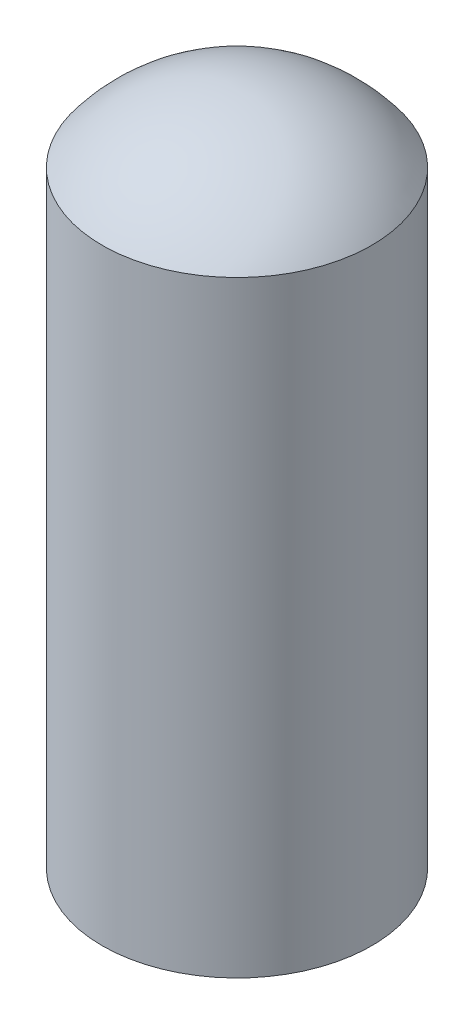
SolidWorks part; units mm, degrees
ref_plane "Front Plane" through (0, 0, 0) normal (0, 0, 1) x (1, 0, 0)
ref_plane "Top Plane" through (0, 0, 0) normal (0, 1, 0) x (1, 0, 0)
ref_plane "Right Plane" through (0, 0, 0) normal (1, 0, 0) x (0, 0, -1)
sketch "Sketch1" plane through (0, 0, 0) normal (0, 0, 1) x (1, 0, 0)
  line L0 (0, 0) -> (-4, 0)
  line L1 (-4, 0) -> (-4, 18)
  line L2 (0, 0) -> (0, 20) construction
  line L5 (0, 20) -> (0, 0)
  arc A0 (-4, 18) -> (0, 20) centre (0, 15) cw
  dimension "D2" = 4
  dimension "D1" = 20
  dimension "D3" = 5
revolve "Revolve1" add sketch "Sketch1" angle 360 about L2
